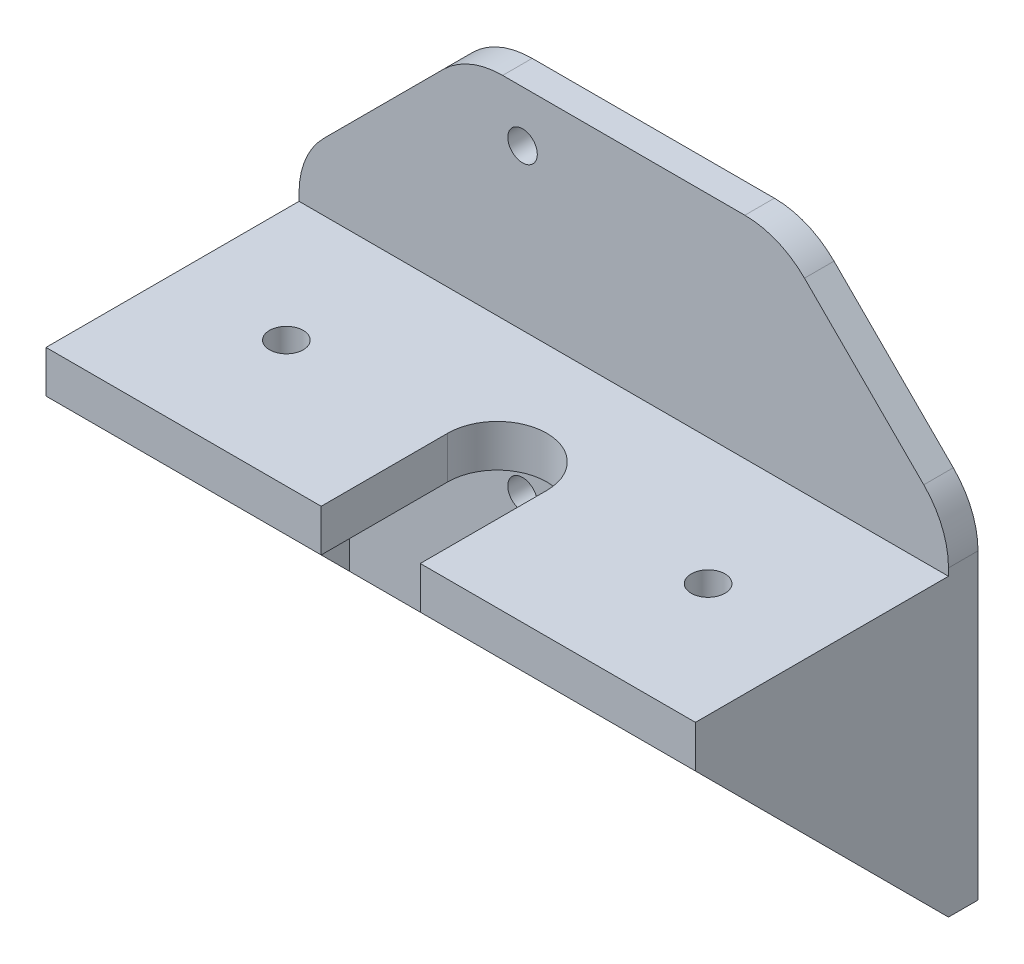
SolidWorks part; units mm, degrees
ref_plane "Front Plane" through (0, 0, 0) normal (0, 0, 1) x (1, 0, 0)
ref_plane "Top Plane" through (0, 0, 0) normal (0, 1, 0) x (1, 0, 0)
ref_plane "Right Plane" through (0, 0, 0) normal (1, 0, 0) x (0, 0, -1)
sketch "Sketch1" plane through (0, 0, 0) normal (0, 0, 1) x (1, 0, 0)
  line L1 (-50.5, 41.85) -> (26.5, 41.85)
  line L2 (-50.5, 41.85) -> (-50.5, -18.15)
  line L3 (-50.5, -18.15) -> (26.5, -18.15)
  line L4 (26.5, 41.85) -> (26.5, -18.15)
  circle A0 centre (-24, 35.8) radius 1.75
  circle A1 centre (-24, 0) radius 1.75
  circle A2 centre (0, 0) radius 1.75
  dimension "D1" = 35.8
  dimension "D2" = 3.5
  dimension "D3" = 24
  dimension "D4" = 77
  dimension "D5" = 26.5
  dimension "D6" = 60
  dimension "D7" = 18.15
extrude "Boss-Extrude1" add sketch "Sketch1" along normal blind 3.5
sketch "Sketch2" plane through (0, 0, 3.5) normal (0, 0, 1) x (1, 0, 0)
  line L0 (-50.5, 41.85) -> (-50.5, -18.15) construction
  line L1 (-50.5, 16.85) -> (26.5, 16.85)
  line L2 (-50.5, 16.85) -> (-50.5, 11.85)
  line L3 (-50.5, 11.85) -> (26.5, 11.85)
  line L4 (26.5, 16.85) -> (26.5, 11.85)
  line L5 (26.5, -18.15) -> (26.5, 41.85) construction
  line L6 (-50.5, -18.15) -> (26.5, -18.15) construction
  dimension "D1" = 5
  dimension "D2" = 30
extrude "Boss-Extrude2" add sketch "Sketch2" along normal blind 30
sketch "Sketch3" plane through (0, 16.85, 0) normal (0, 1, 0) x (1, 0, 0)
  line L0 (-12, -33.5) -> (-12, -3.5) construction
  line L1 (26.5, -33.5) -> (-50.5, -33.5) construction
  line L2 (26.5, -3.5) -> (-50.5, -3.5) construction
  line L3 (-17.875, -18.5) -> (-17.875, -33.5)
  line L4 (-6.125, -18.5) -> (-6.125, -33.5)
  line L5 (-6.125, -33.5) -> (-17.875, -33.5)
  arc A0 (-6.125, -18.5) -> (-17.875, -18.5) centre (-12, -18.5) ccw
  dimension "D1" = 11.75
extrude "Cut-Extrude1" cut sketch "Sketch3" against normal blind 20
sketch "Sketch4" plane through (0, 16.85, 0) normal (0, 1, 0) x (1, 0, 0)
  line L0 (26.5, -18.5) -> (-50.5, -18.5) construction
  line L1 (26.5, -33.5) -> (26.5, -3.5) construction
  line L2 (-50.5, -33.5) -> (-50.5, -3.5) construction
  circle A0 centre (13, -18.5) radius 2
  circle A1 centre (-37, -18.5) radius 2
  dimension "D1" = 4
  dimension "D2" = 50
  dimension "D3" = 13.5
extrude "Cut-Extrude2" cut sketch "Sketch4" against normal blind 20
sketch "Sketch5" plane through (26.5, 0, 0) normal (1, 0, 0) x (0, 0, -1)
  line L0 (-33.5, 11.85) -> (-3.5, -18.15)
rib "Rib2" sketch "Sketch5" sketch "Sketch5" thickness 6 extrusion direction parallel to sketch draft on no parameters "D1"=6
ref_plane "Plane1" through (-12, 0, 0) normal (1, 0, 0) x (0, 0, -1)
mirror "Mirror1" about plane through (-12, 0, 0) normal (1, 0, 0) of "Rib2"
chamfer "Chamfer1" distance 20 angle 45 2 edges at (-50.5, 41.85, 1.75) (26.5, 41.85, 1.75)
fillet "Fillet1" radius 10 4 edges at (-50.5, 21.85, 1.75) (-30.5, 41.85, 1.75) (26.5, 21.85, 1.75) (6.5, 41.85, 1.75)
equation "\"D5@Sketch1\"=(\"D4@Sketch1\"-\"D3@Sketch1\")/2"
equation "\"D7@Sketch1\"=3*(\"D6@Sketch1\"-\"D1@Sketch1\")/4"
equation "\"D3@Sketch4\"=(77-50)/2"
